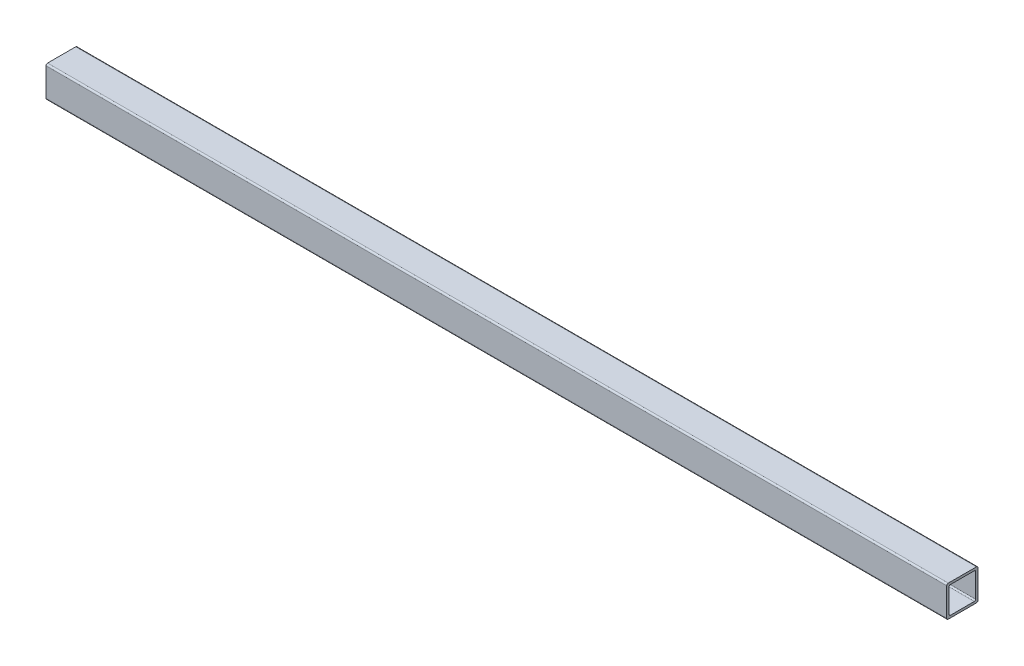
SolidWorks part; units mm, degrees
ref_plane "Front Plane" through (0, 0, 0) normal (0, 0, 1) x (1, 0, 0)
ref_plane "Top Plane" through (0, 0, 0) normal (0, 1, 0) x (1, 0, 0)
ref_plane "Right Plane" through (0, 0, 0) normal (1, 0, 0) x (0, 0, -1)
sketch "Sketch1" plane through (0, 0, 0) normal (0, 0, 1) x (1, 0, 0)
  line L0 (914.4, 0) -> (-914.4, 0)
  dimension "D1" = 1828.8
other "Square tube 2.5X2.5X.188 A500(1)"
ref_plane "Plane2" through (914.4, 0, 0) normal (-1, 0, 0) x (0, -1, 0)
sketch "Sketch12" plane through (914.4, 0, 0) normal (-1, 0, 0) x (0, -1, 0)
  line L0 (-26.9748, 0) -> (-31.75, 0) construction
  line L1 (28.575, -31.75) -> (-28.575, -31.75)
  line L2 (31.75, -28.575) -> (31.75, 28.575)
  line L3 (28.575, 31.75) -> (-28.575, 31.75)
  line L4 (-31.75, -28.575) -> (-31.75, 28.575)
  line L5 (31.75, -31.75) -> (-31.75, 31.75) construction
  line L6 (31.75, 31.75) -> (-31.75, -31.75) construction
  line L7 (24.2773, 26.9748) -> (-24.2773, 26.9748)
  line L8 (26.9748, 24.2773) -> (26.9748, -24.2773)
  line L9 (24.2773, -26.9748) -> (-24.2773, -26.9748)
  line L10 (-26.9748, 24.2773) -> (-26.9748, -24.2773)
  line L11 (26.9748, 26.9748) -> (-26.9748, -26.9748) construction
  line L12 (26.9748, -26.9748) -> (-26.9748, 26.9748) construction
  line L13 (0, -26.9748) -> (0, -31.75) construction
  line L14 (26.9748, -24.2773) -> (26.9748, -31.75) construction
  line L15 (26.9748, 0) -> (31.75, 0) construction
  line L16 (26.9748, -31.75) -> (31.75, -31.75) construction
  arc A0 (-24.2773, -26.9748) -> (-26.9748, -24.2773) centre (-24.2773, -24.2773) cw
  arc A1 (26.9748, -24.2773) -> (24.2773, -26.9748) centre (24.2773, -24.2773) cw
  arc A2 (24.2773, 26.9748) -> (26.9748, 24.2773) centre (24.2773, 24.2773) cw
  arc A3 (-24.2773, 26.9748) -> (-26.9748, 24.2773) centre (-24.2773, 24.2773) ccw
  arc A4 (28.575, -31.75) -> (31.75, -28.575) centre (28.575, -28.575) ccw
  arc A5 (31.75, 28.575) -> (28.575, 31.75) centre (28.575, 28.575) ccw
  arc A6 (-28.575, 31.75) -> (-31.75, 28.575) centre (-28.575, 28.575) ccw
  arc A7 (-28.575, -31.75) -> (-31.75, -28.575) centre (-28.575, -28.575) cw
  point P0 (0, 0)
  point P6 (0, 0)
  point P44 (0, 0)
  dimension "D2" = 2.6975
  dimension "D3" = 3.175
  dimension "D1" = 53.9496
  dimension "Outside Width" = 63.5
  dimension "Ouside Height" = 63.5
  dimension "Wall Thickness" = 4.7752
equation "\"D3@Sketch12\"=\"Outside Width@Sketch12\"*.05"
equation "\"D2@Sketch12\"=\"D1@Sketch12\"*.05"
